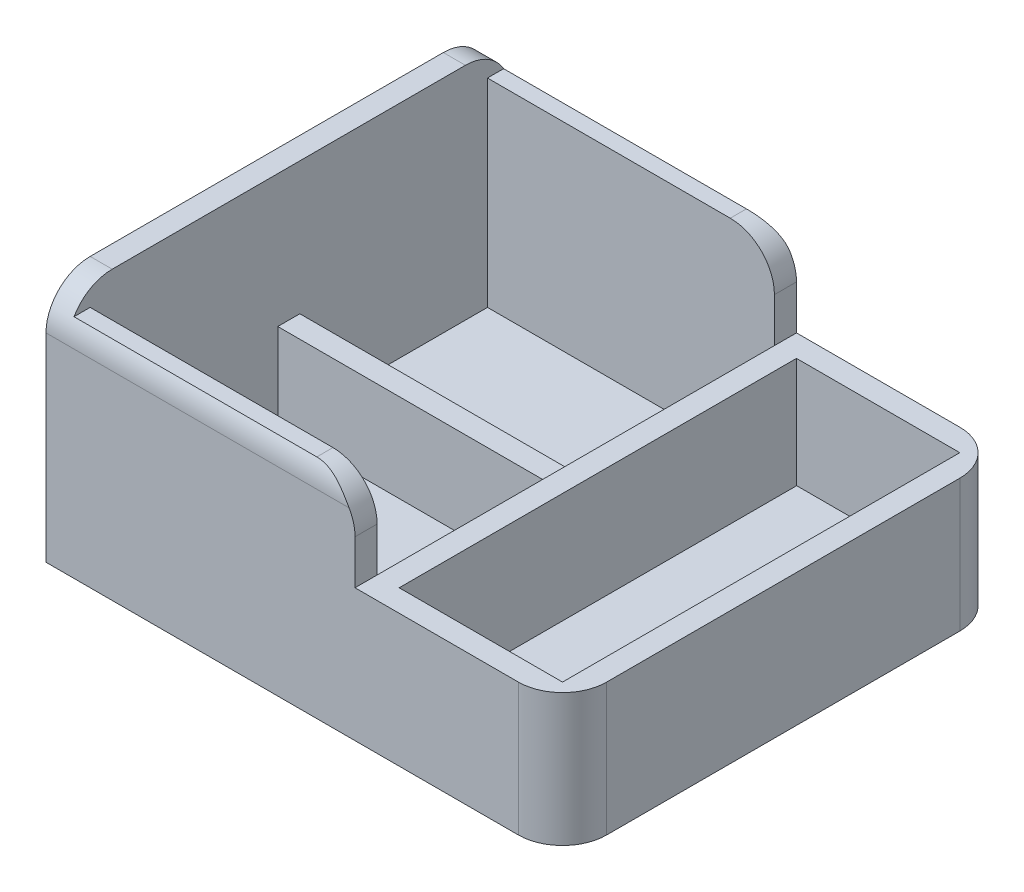
SolidWorks part; units mm, degrees
ref_plane "Alzado" through (0, 0, 0) normal (0, 0, 1) x (1, 0, 0)
ref_plane "Planta" through (0, 0, 0) normal (0, 1, 0) x (1, 0, 0)
ref_plane "Vista lateral" through (0, 0, 0) normal (1, 0, 0) x (0, 0, -1)
sketch "Croquis1" plane through (0, 0, 0) normal (0, 1, 0) x (1, 0, 0)
  line L1 (35, -50) -> (-35, -50)
  line L2 (35, -50) -> (35, 50)
  line L3 (35, 50) -> (-35, 50)
  line L4 (-35, -50) -> (-35, 50)
  line L5 (35, -50) -> (-35, 50) construction
  line L6 (35, 50) -> (-35, -50) construction
  point P0 (0, 0)
  dimension "D1" = 100
  dimension "D2" = 70
extrude "Saliente-Extruir2" add sketch "Croquis1" along normal blind 5
sketch "Croquis2" plane through (0, 5, 0) normal (0, 1, 0) x (1, 0, 0)
  line L0 (-35, -50) -> (35, -50) construction
  line L1 (-35, 50) -> (-30, 50)
  line L2 (-35, 50) -> (-35, -50)
  line L3 (-35, -50) -> (-30, -50)
  line L4 (-30, 50) -> (-30, -50)
  dimension "D1" = 5
extrude "Saliente-Extruir3" add sketch "Croquis2" along normal blind 50
sketch "Croquis3" plane through (0, 5, 0) normal (0, 1, 0) x (1, 0, 0)
  line L0 (-30, -50) -> (-30, 50) construction
  line L1 (35, -50) -> (-30, -50)
  line L2 (35, -50) -> (35, -45)
  line L3 (35, -45) -> (-30, -45)
  line L4 (-30, -50) -> (-30, -45)
  dimension "D1" = 5
extrude "Saliente-Extruir4" add sketch "Croquis3" along normal blind 45
sketch "Croquis4" plane through (0, 5, 0) normal (0, 1, 0) x (1, 0, 0)
  line L0 (-30, -45) -> (-30, 50) construction
  line L1 (35, 50) -> (-30, 50)
  line L2 (35, 50) -> (35, 45)
  line L3 (35, 45) -> (-30, 45)
  line L4 (-30, 50) -> (-30, 45)
  dimension "D1" = 5
extrude "Saliente-Extruir5" add sketch "Croquis4" along normal blind 45
sketch "Croquis5" plane through (0, 0, 0) normal (0, -1, 0) x (1, 0, 0)
  line L1 (35, 50) -> (40, 50)
  line L2 (35, 50) -> (35, -50)
  line L3 (35, -50) -> (40, -50)
  line L4 (40, 50) -> (40, -50)
  dimension "D1" = 5
extrude "Saliente-Extruir6" add sketch "Croquis5" against normal blind 30
fillet "Redondeo2" radius 10 1 edges at (35, 50, 47.5)
fillet "Redondeo3" radius 10 1 edges at (35, 50, -47.5)
fillet "Redondeo4" radius 10 1 edges at (-32.5, 55, 50)
fillet "Redondeo5" radius 10 1 edges at (-32.5, 55, -50)
ref_plane "Plano1" through (0, 0, 0) normal (0, 0, 1) x (1, 0, 0)
sketch "Croquis10" plane through (0, 0, 0) normal (0, 0, 1) x (1, 0, 0)
  line L0 (35, 30) -> (35, -4.9499) construction
  line L1 (-30, 55) -> (-30, -4.9499) construction
  line L2 (-41.3053, 5) -> (57.1354, 5) construction
  line L3 (-35, 0) -> (40, 0) construction
  line L4 (35, 5) -> (-30, 5)
  line L5 (-30, 5) -> (-30, 25)
  line L6 (-30, 25) -> (35, 25)
  line L7 (35, 25) -> (35, 5)
  point P10 (-30, 5)
  point P12 (35, 5)
  dimension "D1" = 5
  dimension "D2" = 20
extrude "Saliente-Extruir8" add sketch "Croquis10" along normal blind 2.5 and the other way blind 2.5
sketch "Croquis11" plane through (40, 0, 0) normal (1, 0, 0) x (0, 0, -1)
  line L0 (-50, 30) -> (-45, 30)
  line L1 (-45, 30) -> (-45, 5)
  line L2 (-45, 50) -> (-45, 5) construction
  line L3 (-45, 5) -> (45.0445, 5)
  line L4 (45.0445, 5) -> (45, 30)
  line L5 (45, 30) -> (50, 30)
  line L6 (50, 30) -> (50, 0)
  line L7 (50, 0) -> (-50, 0)
  line L8 (-50, 0) -> (-50, 30)
extrude "Saliente-Extruir9" add sketch "Croquis11" along normal blind 37
sketch "Croquis12" plane through (0, 0, 0) normal (0, -1, 0) x (1, 0, 0)
  line L1 (77, -50) -> (82, -50)
  line L2 (77, -50) -> (77, 50)
  line L3 (77, 50) -> (82, 50)
  line L4 (82, -50) -> (82, 50)
  dimension "D1" = 5
extrude "Saliente-Extruir10" add sketch "Croquis12" against normal blind 30
fillet "Redondeo10" radius 10 1 edges at (77, 5, -0.0223)
fillet "Redondeo11" radius 10 1 edges at (82, 15, -50)
fillet "Redondeo13" radius 10 1 edges at (82, 15, 50)
fillet "Redondeo16" radius 10 2 edges at (35, 5, 23.75) (35, 5, -23.75)
